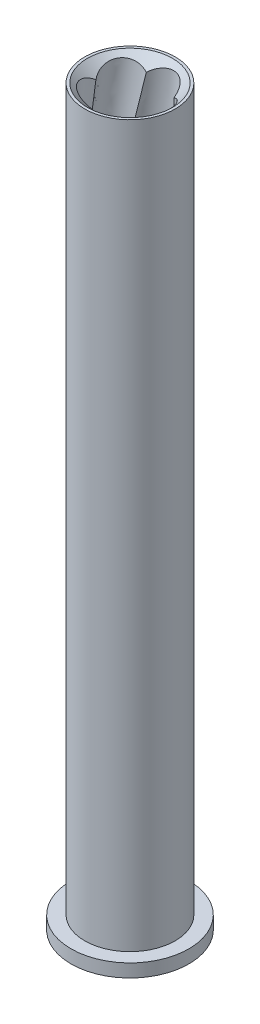
SolidWorks part; units mm, degrees
ref_plane "Front Plane" through (0, 0, 0) normal (0, 0, 1) x (1, 0, 0)
ref_plane "Top Plane" through (0, 0, 0) normal (0, 1, 0) x (1, 0, 0)
ref_plane "Right Plane" through (0, 0, 0) normal (1, 0, 0) x (0, 0, -1)
sketch "Sketch1" plane through (0, 0, 0) normal (0, 1, 0) x (1, 0, 0)
  circle A0 centre (0, 0) radius 4.5
  dimension "D1" = 9
extrude "Boss-Extrude1" add sketch "Sketch1" along normal blind 1
sketch "Sketch2" plane through (0, 1, 0) normal (0, 1, 0) x (1, 0, 0)
  circle A0 centre (0, 0) radius 3.45
  dimension "D1" = 6.9
extrude "Boss-Extrude2" add sketch "Sketch2" along normal blind 55
sketch "Sketch3" plane through (0, 56, 0) normal (0, 1, 0) x (1, 0, 0)
  circle A0 centre (0, 0) radius 2
  dimension "D1" = 4
extrude "Cut-Extrude1" cut sketch "Sketch3" against normal through all
chamfer "Chamfer1" distance 1 angle 30 1 edges at (0, 0, 2)
ref_axis "Axis1" through (0, 1, 0) along (0, 1, 0)
sketch "Sketch4" plane through (0, 0, 0) normal (0, 1, 0) x (1, 0, 0)
  circle A2 centre (0, 0) radius 2
  circle A3 centre (0, 0) radius 2
  dimension "D1" = 0
curve "Helix/Spiral1" pitch 75 height 100 turns 1.3333
sketch "Sketch5" plane through (0, 0, 0) normal (0, 1, 0) x (1, 0, 0)
  circle A0 centre (0, 0) radius 1.4 construction
  circle A1 centre (0, -1.4) radius 1.5
  dimension "D1" = 2.8
  dimension "D2" = 3
sweep "Cut-Sweep1" cut profiles "Sketch5" path "Helix/Spiral1"
pattern_circular "CirPattern1" count 5 over 360 about axis through (0, 1, 0) along (0, 1, 0) of "Cut-Sweep1"
sketch "Sketch6" plane through (0, 0, 0) normal (1, 0, 0) x (0, 0, -1)
  line L8 (0, 56) -> (-3.25, 56)
  line L9 (0, 1) -> (0, 56) construction
  line L10 (1.443, 56) -> (-1.3622, 56) construction
  line L11 (3.45, 56) -> (-3.45, 56) construction
  line L12 (-3.25, 56) -> (0, 52.75)
  line L13 (0, 52.75) -> (0, 56)
  line L14 (-3.45, 56) -> (-3.45, 1) construction
  dimension "D1" = 45
  dimension "D2" = 0.2
revolve "Cut-Revolve1" cut sketch "Sketch6" angle 360 about axis through (0, 1, 0) along (0, 1, 0)
